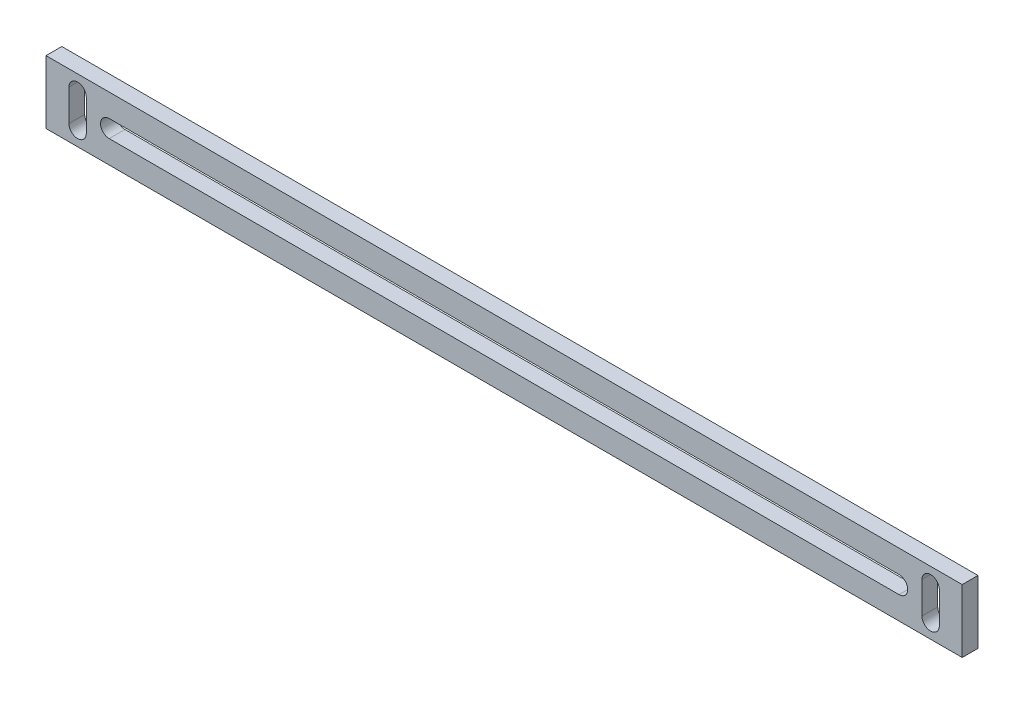
SolidWorks part; units mm, degrees
material "ABS"
ref_plane "前视基准面" through (0, 0, 0) normal (0, 0, 1) x (1, 0, 0)
ref_plane "上视基准面" through (0, 0, 0) normal (0, 1, 0) x (1, 0, 0)
ref_plane "右视基准面" through (0, 0, 0) normal (1, 0, 0) x (0, 0, -1)
other "Configuration Table"
sketch "草图1" plane through (0, 0, 0) normal (0, 0, 1) x (1, 0, 0)
  line L0 (0, 0) -> (0, 10)
  line L1 (0, 10) -> (-145, 10)
  line L2 (-145, 10) -> (-145, -10)
  line L3 (-145, -10) -> (145, -10)
  line L4 (145, -10) -> (145, 10)
  line L5 (145, 10) -> (0, 10)
  dimension "D1" = 290
  dimension "D2" = 20
  dimension "D3" = 10
extrude "凸台-拉伸1" add sketch "草图1" along normal blind 5
sketch "草图3" plane through (0, 0, 0) normal (0, 0, -1) x (-1, 0, 0)
  line L0 (-145, 0) -> (-135, 0)
  line L1 (-145, -10) -> (-145, 10) construction
  line L2 (-135, 0) -> (-135, 10)
  line L3 (-145, 10) -> (145, 10) construction
  line L4 (-135, 0) -> (-135, -10)
  line L5 (145, -10) -> (-145, -10) construction
  line L6 (-135, 0) -> (-125, 0)
  line L7 (145, 0) -> (135, 0)
  line L8 (145, 10) -> (145, -10) construction
  line L9 (135, 0) -> (135, 10)
  line L10 (135, 0) -> (135, -10)
  line L11 (135, 0) -> (125, 0)
  line L12 (125, 0) -> (-125, 0)
  line L13 (-125, 0) -> (125, 0) construction
  line L14 (-125, 2.75) -> (125, 2.75)
  line L15 (-125, -2.75) -> (125, -2.75)
  line L16 (-135, 0) -> (-135, -5)
  line L17 (-135, -5) -> (-135, 5)
  line L18 (135, -5) -> (135, 5)
  line L19 (-135, -5) -> (-135, 5) construction
  line L20 (-137.75, -5) -> (-137.75, 5)
  line L21 (-132.25, -5) -> (-132.25, 5)
  line L22 (135, -5) -> (135, 5) construction
  line L23 (132.25, -5) -> (132.25, 5)
  line L24 (137.75, -5) -> (137.75, 5)
  arc A0 (-125, 2.75) -> (-125, -2.75) centre (-125, 0) ccw
  arc A1 (125, -2.75) -> (125, 2.75) centre (125, 0) ccw
  arc A2 (-137.75, -5) -> (-132.25, -5) centre (-135, -5) ccw
  arc A3 (-132.25, 5) -> (-137.75, 5) centre (-135, 5) ccw
  arc A4 (132.25, -5) -> (137.75, -5) centre (135, -5) ccw
  arc A5 (137.75, 5) -> (132.25, 5) centre (135, 5) ccw
  point P19 (0, 0)
  point P28 (-135, 0)
  point P33 (135, 0)
  dimension "D1" = 125
  dimension "D2" = 10
  dimension "D3" = 10
  dimension "D4" = 10
extrude "切除-拉伸1" cut sketch "草图3" against normal blind 5 contours L21 A3 L2 L6 | L2 A3 L20 L0 | L20 A2 L4 L0 | L4 A2 L21 L6 | L15 A1 L11 L12 L6 A0 | L11 A1 L14 A0 L6 L12 | L24 A5 L9 L7 | L9 A5 L23 L11 | L23 A4 L10 L11 | L10 A4 L24 L7
